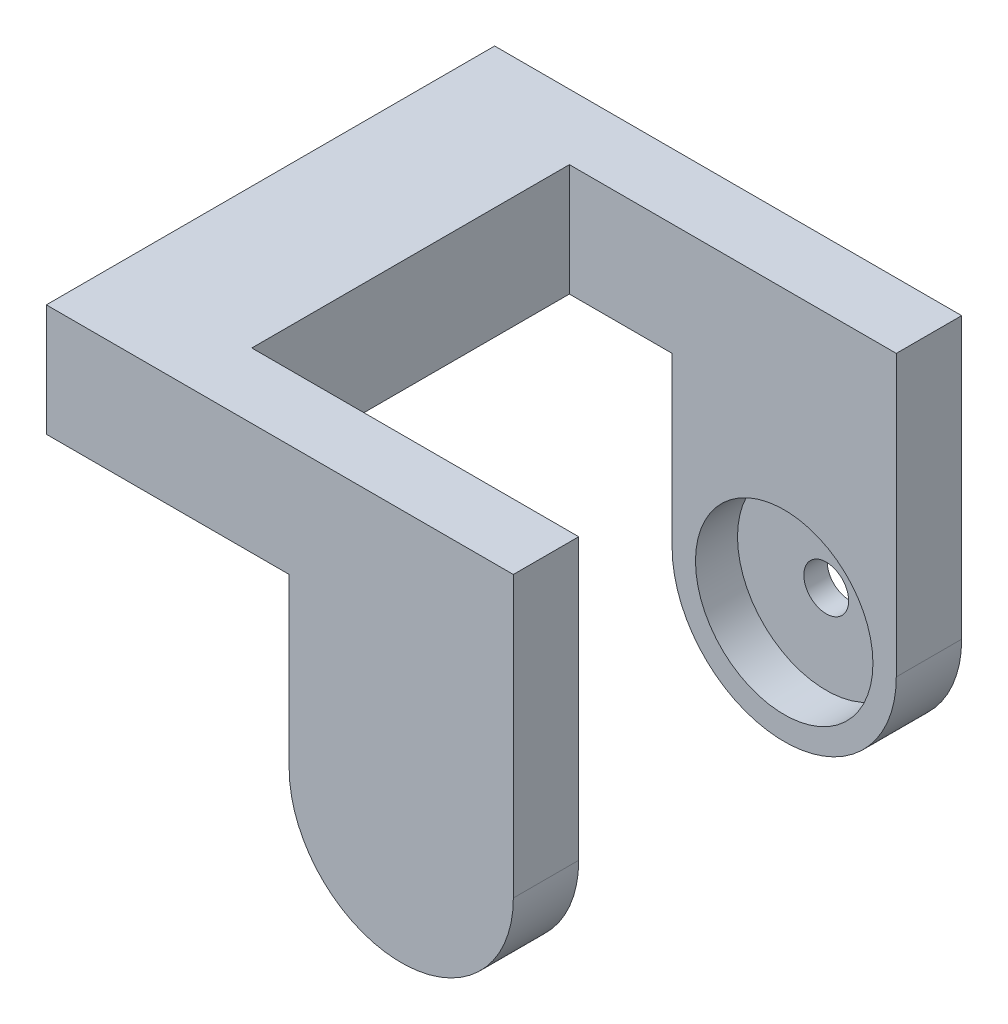
SolidWorks part; units mm, degrees
ref_plane "Front Plane" through (0, 0, 0) normal (0, 0, 1) x (1, 0, 0)
ref_plane "Top Plane" through (0, 0, 0) normal (0, 1, 0) x (1, 0, 0)
ref_plane "Right Plane" through (0, 0, 0) normal (1, 0, 0) x (0, 0, -1)
sketch "Sketch1" plane through (0, 0, 0) normal (0, 0, 1) x (1, 0, 0)
  line L0 (0, 0) -> (0, 30) construction
  line L1 (-12, 0) -> (-12, 30)
  line L2 (12, 0) -> (12, 30)
  line L3 (-12, 30) -> (12, 30)
  line L5 (-12, 30) -> (12, 30)
  line L6 (-12, 30) -> (-12, 26)
  line L7 (-12, 26) -> (12, 26)
  line L8 (12, 30) -> (12, 26)
  circle A0 centre (0, 0) radius 9.5
  arc A2 (-12, 0) -> (12, 0) centre (0, 0) ccw
  arc A3 (12, 30) -> (-12, 30) centre (0, 30) ccw
  point P3 (0, 15)
  dimension "D1" = 19
  dimension "D2" = 30
  dimension "D3" = 12
  dimension "D4" = 4
extrude "Boss-Extrude1" add sketch "Sketch1" against normal blind 48
sketch "Sketch2" plane through (-12, 0, 0) normal (-1, 0, 0) x (0, 0, 1)
  line L0 (-48, -12) -> (0, -12) construction
  line L1 (-7, -12) -> (-41, -12)
  line L2 (-7, -12) -> (-7, 18)
  line L3 (-7, 18) -> (-41, 18)
  line L4 (-41, -12) -> (-41, 18)
  line L5 (-48, 0) -> (-48, 30) construction
  line L6 (0, -12) -> (0, 0) construction
  dimension "D1" = 7
  dimension "D2" = 7
  dimension "D3" = 30
extrude "Cut-Extrude1" cut sketch "Sketch2" against normal through all
sketch "Sketch3" plane through (0, 0, -48) normal (0, 0, -1) x (-1, 0, 0)
  circle A0 centre (0, 0) radius 9.5
  circle A1 centre (0, 0) radius 2.4
  dimension "D1" = 4.8
  dimension "D2" = 19
extrude "Boss-Extrude2" add sketch "Sketch3" against normal blind 2.5
sketch "Sketch4" plane through (0, 0, 0) normal (0, 0, 1) x (1, 0, 0)
  circle A0 centre (0, 0) radius 9.5
  circle A1 centre (0, 0) radius 4.2
  dimension "D1" = 19
  dimension "D2" = 8.4
extrude "Boss-Extrude3" add sketch "Sketch4" against normal blind 7
sketch "Sketch5" plane through (0, 0, 0) normal (0, 0, 1) x (1, 0, 0)
  circle A0 centre (0, 0) radius 4.2
extrude "Boss-Extrude4" add sketch "Sketch5" against normal blind 11
sketch "Sketch6" plane through (0, 0, -48) normal (0, 0, -1) x (-1, 0, 0)
  line L0 (0, 0) -> (30, 0)
  line L1 (-12, 30) -> (12, 30)
  line L2 (-12, 30) -> (-12, 0)
  line L3 (-12, 0) -> (12, 0)
  line L4 (12, 30) -> (12, 0)
  line L5 (-9.5, 0) -> (9.5, 0)
  line L6 (-9.5, 0) -> (-9.5, 30)
  line L7 (-9.5, 30) -> (9.5, 30)
  line L8 (9.5, 0) -> (9.5, 30)
  line L9 (30, 0) -> (0, 0)
  line L10 (0, 0) -> (21.2132, 21.2132)
  line L12 (12, 30) -> (38, 30)
  line L13 (12, 30) -> (12, 18)
  line L14 (12, 18) -> (38, 18)
  line L15 (38, 30) -> (38, 18)
  circle A0 centre (0, 0) radius 12
  circle A3 centre (0, 0) radius 9.5 construction
  dimension "D1" = 50
  dimension "D3" = 45
extrude "Boss-Extrude5" add sketch "Sketch6" against normal blind 48
sketch "Sketch7" plane through (0, 30, 0) normal (0, 1, 0) x (1, 0, 0)
  line L1 (12, 41) -> (-23, 41)
  line L2 (12, 41) -> (12, 7)
  line L3 (12, 7) -> (-23, 7)
  line L4 (-23, 41) -> (-23, 7)
  dimension "D1" = 35
extrude "Cut-Extrude2" cut sketch "Sketch7" against normal blind 14.5
